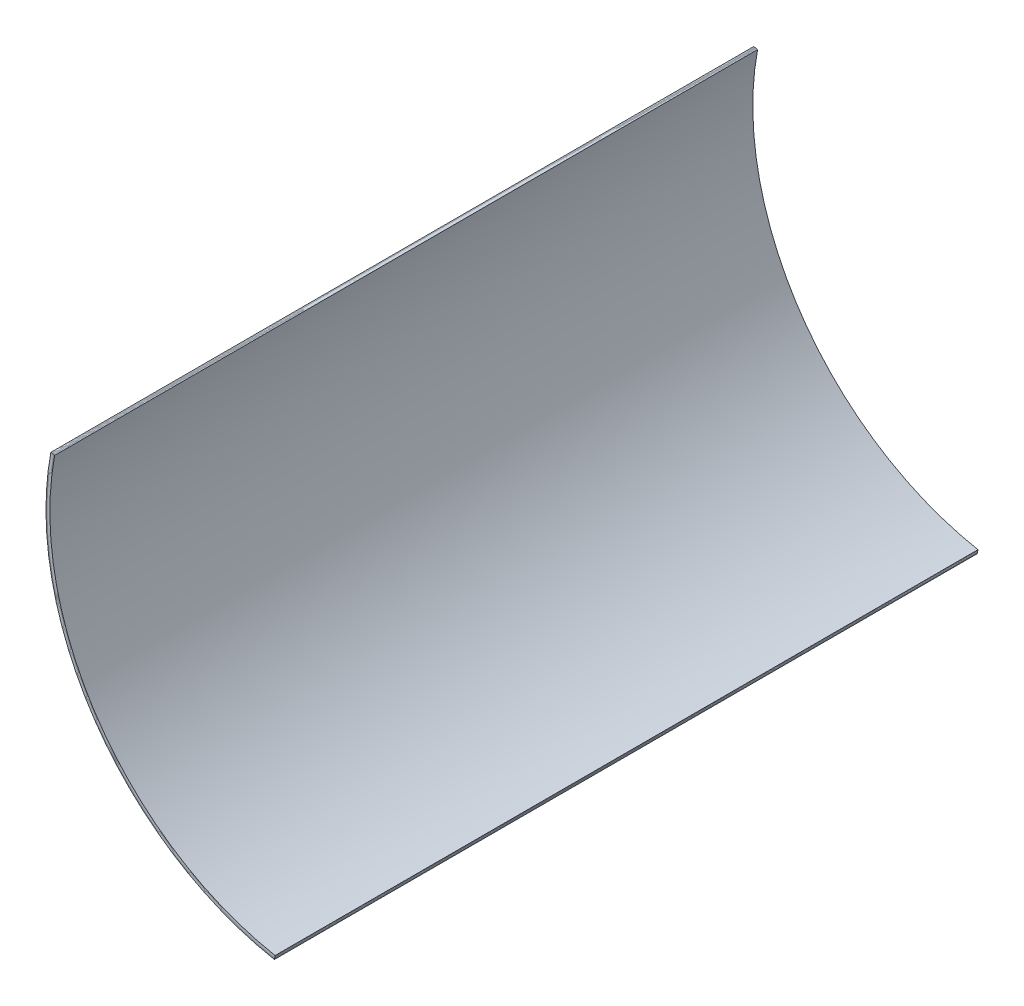
SolidWorks part; units mm, degrees
ref_plane "Front Plane" through (0, 0, 0) normal (0, 0, 1) x (1, 0, 0)
ref_plane "Top Plane" through (0, 0, 0) normal (0, 1, 0) x (1, 0, 0)
ref_plane "Right Plane" through (0, 0, 0) normal (1, 0, 0) x (0, 0, -1)
sketch "Sketch1" plane through (0, 0, 0) normal (0, 0, 1) x (1, 0, 0)
  arc A0 (-44.7389, -237.1163) -> (-237.1163, 44.7389) centre (0, 0) cw
  arc A1 (-44.8896, -237.915) -> (-237.915, 44.8896) centre (0, 0) cw
  dimension "D1" = 0.8128
  dimension "D2" = 241.3
extrude "Extrude-Thin1" add sketch "Sketch1" along normal blind 607.06 thin
